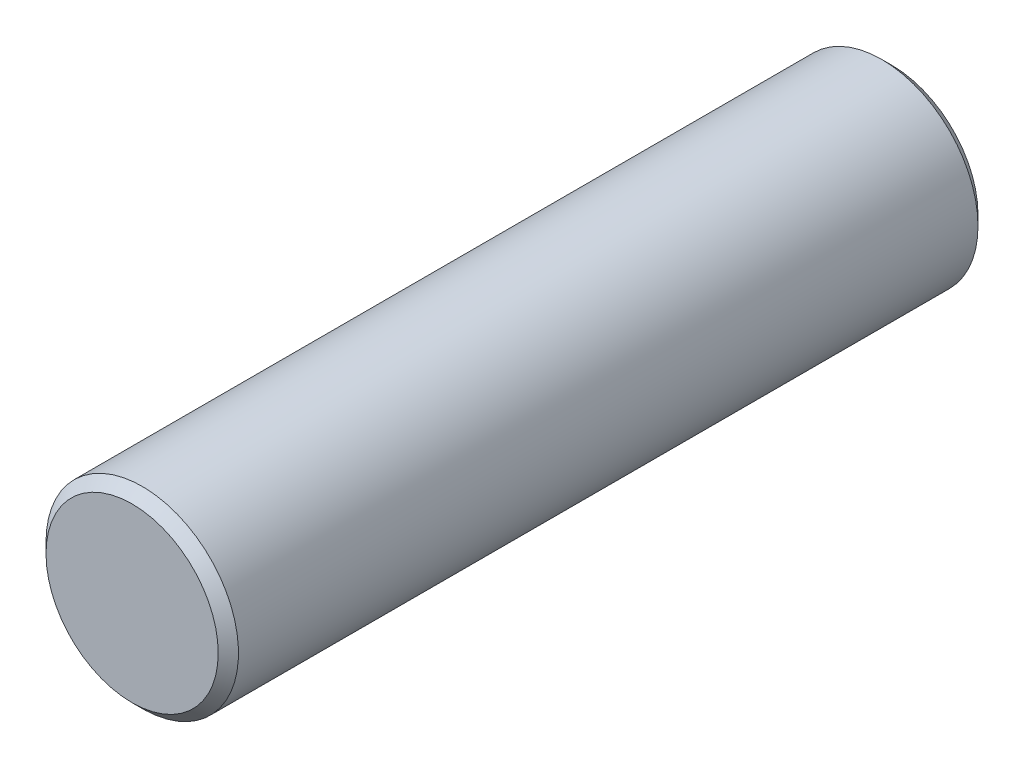
SolidWorks part; units mm, degrees
ref_plane "Front Plane" through (0, 0, 0) normal (0, 0, 1) x (1, 0, 0)
ref_plane "Top Plane" through (0, 0, 0) normal (0, 1, 0) x (1, 0, 0)
ref_plane "Right Plane" through (0, 0, 0) normal (1, 0, 0) x (0, 0, -1)
sketch "Sketch1" plane through (0, 0, 0) normal (0, 0, 1) x (1, 0, 0)
  circle A0 centre (0, 0) radius 4.826
  dimension "D1" = 9.652
extrude "Boss-Extrude1" add sketch "Sketch1" along normal blind 38.1
chamfer "Chamfer1" distance 0.508 angle 45 2 edges at (4.826, 0, 0) (4.826, 0, 38.1)
